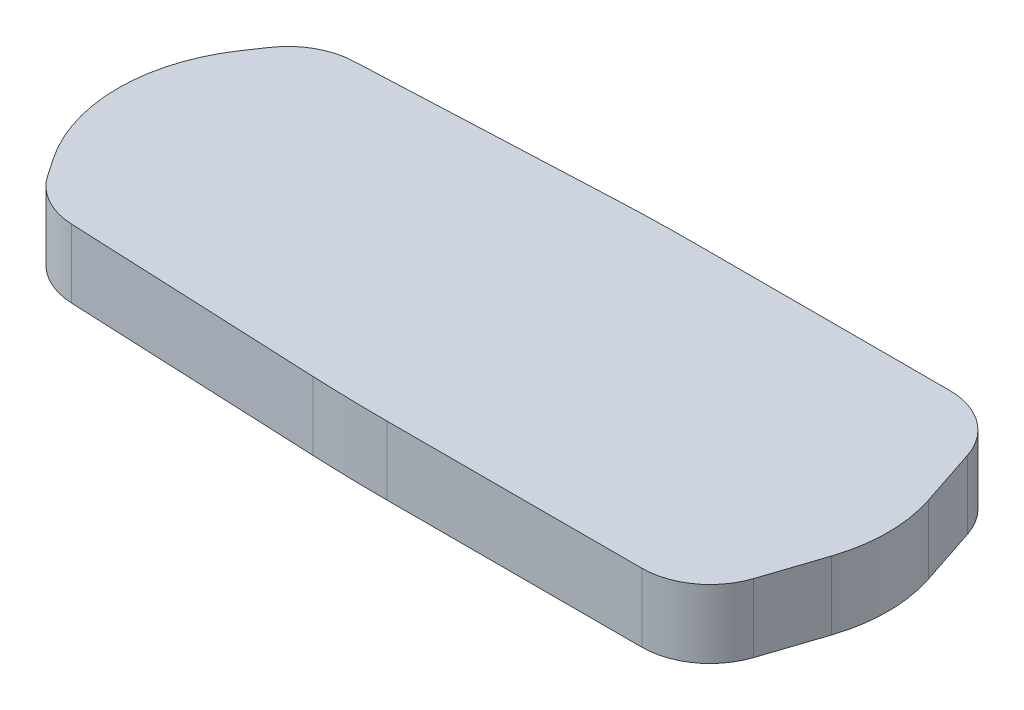
SolidWorks part; units mm, degrees
ref_plane "Спереди" through (0, 0, 0) normal (0, 0, 1) x (1, 0, 0)
ref_plane "Сверху" through (0, 0, 0) normal (0, 1, 0) x (1, 0, 0)
ref_plane "Справа" through (0, 0, 0) normal (1, 0, 0) x (0, 0, -1)
sketch "Эскиз1" plane through (0, 0, 0) normal (0, 1, 0) x (1, 0, 0)
  line L0 (0, 0) -> (450, 0) construction
  line L1 (0, 0) -> (0, 90) construction
  line L2 (450, 0) -> (450, 90) construction
  line L3 (0, 90) -> (450, 90) construction
  line L5 (16.8029, 54.7195) -> (23.7303, 64.9356)
  line L6 (55.0608, 82.4471) -> (202.8106, 89.0138)
  line L7 (247.2113, 90) -> (396.1111, 90)
  line L8 (450, 0) -> (492.8913, 0) construction
  line L9 (445.4361, 28.2961) -> (434.0827, 62.5761)
  line L10 (445.4361, -28.2961) -> (434.0827, -62.5761)
  line L11 (247.2113, -90) -> (396.1111, -90)
  line L12 (55.0608, -82.4471) -> (202.8106, -89.0138)
  line L13 (16.8029, -54.7195) -> (23.7303, -64.9356)
  arc A0 (445.4361, -28.2961) -> (445.4361, 28.2961) centre (360, 0) ccw
  arc A1 (247.2113, 90) -> (202.8106, 89.0138) centre (247.2113, -910) ccw
  arc A2 (16.8029, 54.7195) -> (16.8029, -54.7195) centre (97.5, 0) ccw
  arc A3 (23.7303, 64.9356) -> (55.0608, 82.4471) centre (56.8368, 42.4866) cw
  arc A4 (396.1111, 90) -> (434.0827, 62.5761) centre (396.1111, 50) cw
  arc A5 (396.1111, -90) -> (434.0827, -62.5761) centre (396.1111, -50) ccw
  arc A6 (247.2113, -90) -> (202.8106, -89.0138) centre (247.2113, 910) cw
  arc A7 (23.7303, -64.9356) -> (55.0608, -82.4471) centre (56.8368, -42.4866) ccw
  point P10 (360, 90)
  point P11 (425, 90)
  point P15 (225, 90)
  point P18 (35, 81.5556)
  point P24 (425, 90)
  dimension "D3" = 40
  dimension "D4" = 180
  dimension "D6" = 1000
  dimension "D7" = 195
  dimension "D8" = 40
  dimension "D5" = 25
extrude "Бобышка-Вытянуть1" add sketch "Эскиз1" along normal blind 40
sketch "Эскиз3" plane through (0, 40, 0) normal (0, 1, 0) x (1, 0, 0)
  line L0 (0, 0) -> (450, 0) construction
  line L1 (247.2113, 90) -> (247.2113, -90) construction
  line L2 (396.1111, 90) -> (247.2113, 90) construction
  line L3 (281.1829, 78.7667) -> (251.2031, 17.2922)
  line L4 (299.1592, 90) -> (321.6612, 90)
  line L5 (321.6612, 90) -> (-21.7456, 94.1539)
  line L6 (-21.7456, 94.1539) -> (-22.8845, 0)
  line L7 (-21.7456, -94.1539) -> (-22.8845, 0)
  line L8 (281.1829, -78.7667) -> (251.2031, -17.2922)
  line L9 (299.1592, -90) -> (321.6612, -90)
  line L10 (321.6612, -90) -> (-21.7456, -94.1539)
  arc A0 (445.4361, -28.2961) -> (445.4361, 28.2961) centre (360, 0) ccw construction
  arc A1 (251.2031, 17.2922) -> (251.2031, -17.2922) centre (286.6612, 0) ccw
  arc A2 (281.1829, 78.7667) -> (299.1592, 90) centre (299.1592, 70) cw
  arc A3 (281.1829, -78.7667) -> (299.1592, -90) centre (299.1592, -70) ccw
  point P10 (286.6612, 90)
  point P11 (321.6612, 90)
  point P21 (286.6612, 90)
  dimension "D2" = 20
  dimension "D1" = 35
